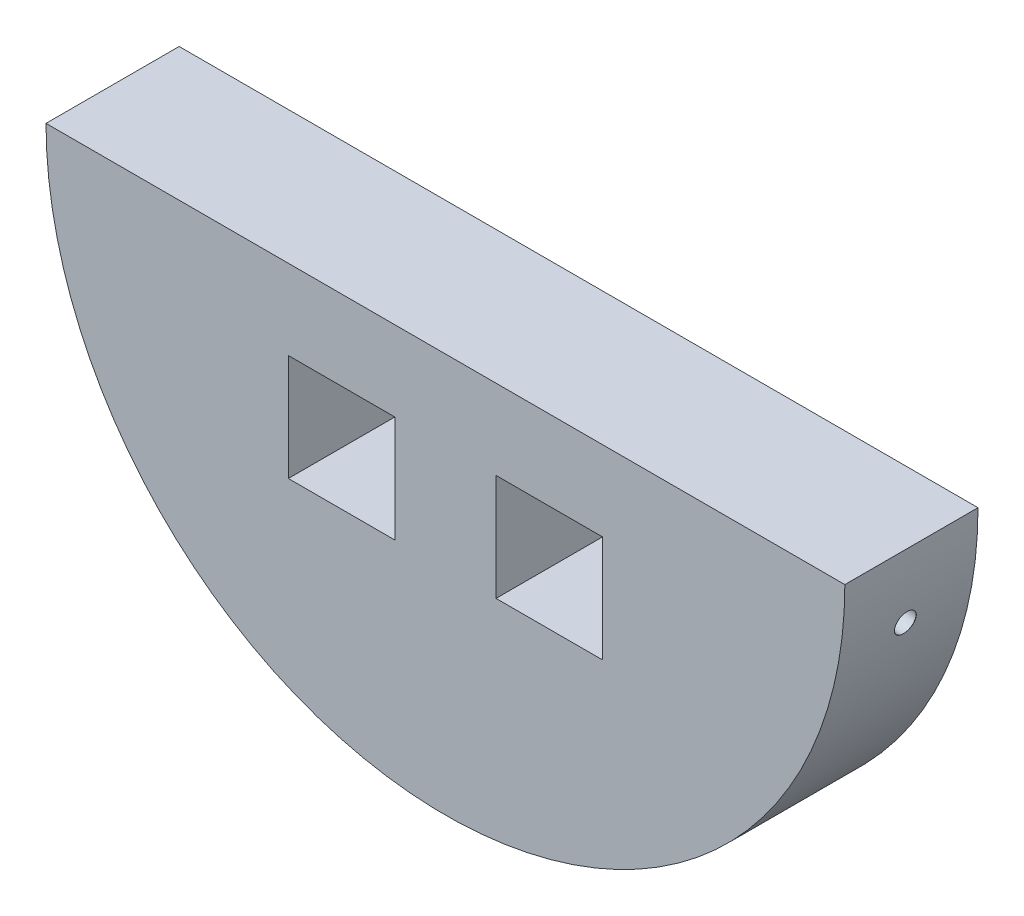
SolidWorks part; units mm, degrees
ref_plane "Front Plane" through (0, 0, 0) normal (0, 0, 1) x (1, 0, 0)
ref_plane "Top Plane" through (0, 0, 0) normal (0, 1, 0) x (1, 0, 0)
ref_plane "Right Plane" through (0, 0, 0) normal (1, 0, 0) x (0, 0, -1)
sketch "Sketch1" plane through (0, 0, 0) normal (0, 0, 1) x (1, 0, 0)
  line L0 (-150, 0) -> (0, 0)
  line L3 (-65.5, -35) -> (-45.5, -35)
  line L4 (-65.5, -35) -> (-65.5, -15)
  line L5 (-65.5, -15) -> (-45.5, -15)
  line L6 (-45.5, -35) -> (-45.5, -15)
  line L7 (-104.5, -35) -> (-84.5, -35)
  line L8 (-104.5, -35) -> (-104.5, -15)
  line L9 (-104.5, -15) -> (-84.5, -15)
  line L10 (-84.5, -35) -> (-84.5, -15)
  arc A1 (-150, 0) -> (0, 0) centre (-75, 0) ccw
  dimension "D1" = 19
  dimension "D7" = 75
  dimension "D2" = 15
  dimension "D3" = 9.5
  dimension "D4" = 20
extrude "Boss-Extrude1" add sketch "Sketch1" along normal blind 25
hole_wizard "Ø4.0mm Dowel Hole2" positions "3DSketch2" profile "Sketch4" hole size "Ø4.0" standard "ANSI Metric"
sketch3d "3DSketch2"
  line L2 (0, 0, 25) -> (0, 0, 0) construction
  line L4 (0, 0, 25) -> (0, 0, 0) construction
  line L5 (0, 0, 12.5) -> (-1.1394, -13.0236, 12.5) construction
  line L8 (-75, 0, 0) -> (-75, 0, 25) construction
  line L9 (0, 0, 0) -> (-150, 0, 0) construction
  line L10 (0, 0, 25) -> (-150, 0, 25) construction
  line L12 (-75, 0, 12.5) -> (-1.1394, -13.0236, 12.5) construction
  line L16 (-75, 0, 12.5) -> (0, 0, 12.5) construction
  point P0 (-1.1394, -13.0236, 12.5)
  point P16 (-1.1394, -13.0236, 12.5)
  point P23 (-1.1394, -13.0236, 12.5)
  point P25 (-1.1394, -13.0236, 12.5)
  dimension "D1" = 10
sketch "Sketch4" plane through (-1.1394, -13.0236, 12.5) normal (0, 0, 1) x (0.1736, 0.9848, 0)
  line L0 (0, 0) -> (0, 17.2017)
  line L1 (0, 17.2017) -> (2, 16)
  line L2 (2, 16) -> (2, 0.025)
  line L3 (2, 0.025) -> (2.025, 0)
  line L5 (2.025, 0) -> (0, 0)
  line L6 (-2, 0.025) -> (-2.025, 0) construction
  line L10 (0, 17.2017) -> (-2, 16) construction
  line L11 (0, -6.35) -> (0, 107.95) construction
  dimension "Hole Dia." = 4
  dimension "Hole Depth" = 16
  dimension "Near C'Sink Dia." = 4.05
  dimension "Near C'Sink Angle" = 90
  dimension "Drill Angle" = 118
pattern_circular "CirPattern1" count 5 over 160 about axis through (-75, 0, 0) along (0, 0, 1) of "Ø4.0mm Dowel Hole2"
chamfer "Chamfer1" distance 15 angle 30 2 edges at (-94.5, -15, 0) (-55.5, -15, 0)
